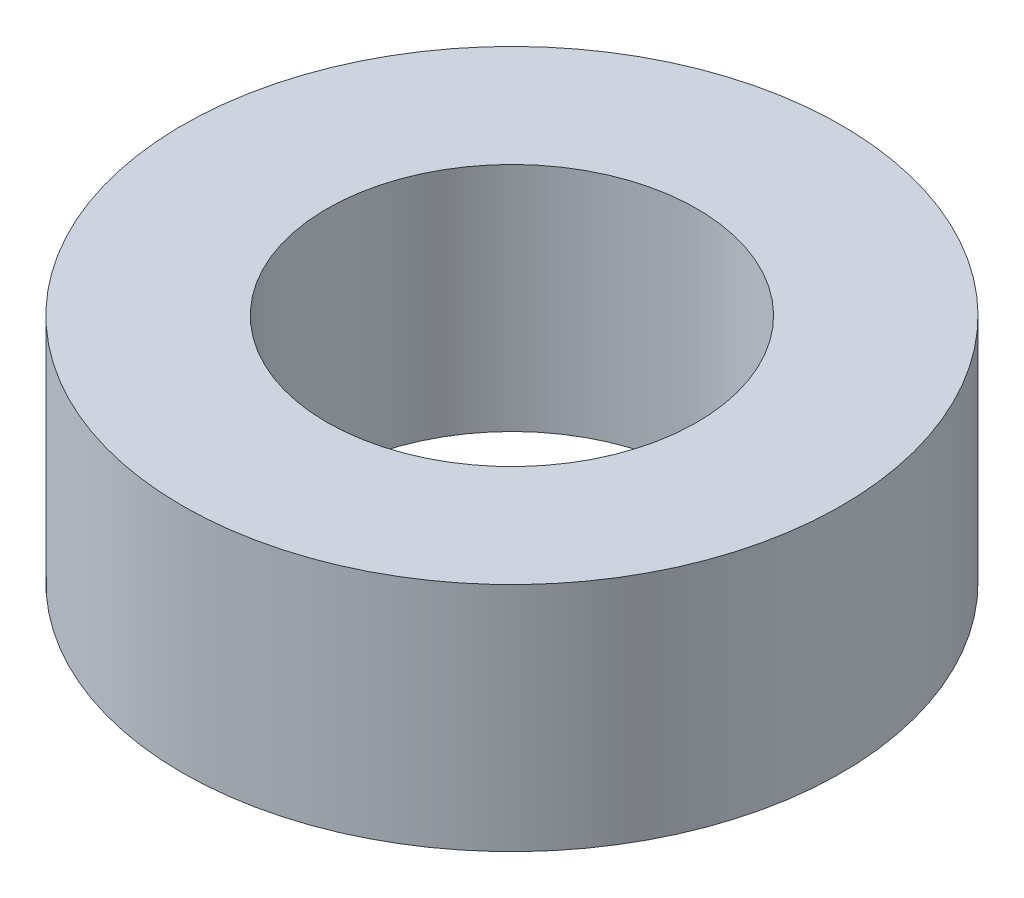
SolidWorks part; units mm, degrees
ref_plane "Front Plane" through (0, 0, 0) normal (0, 0, 1) x (1, 0, 0)
ref_plane "Top Plane" through (0, 0, 0) normal (0, 1, 0) x (1, 0, 0)
ref_plane "Right Plane" through (0, 0, 0) normal (1, 0, 0) x (0, 0, -1)
sketch "Sketch1" plane through (0, 0, 0) normal (0, 1, 0) x (1, 0, 0)
  circle A0 centre (0, 0) radius 16
  circle A1 centre (0, 0) radius 28.5
  dimension "D1" = 57
  dimension "D2" = 32
extrude "Boss-Extrude1" add sketch "Sketch1" along normal mid plane 20
